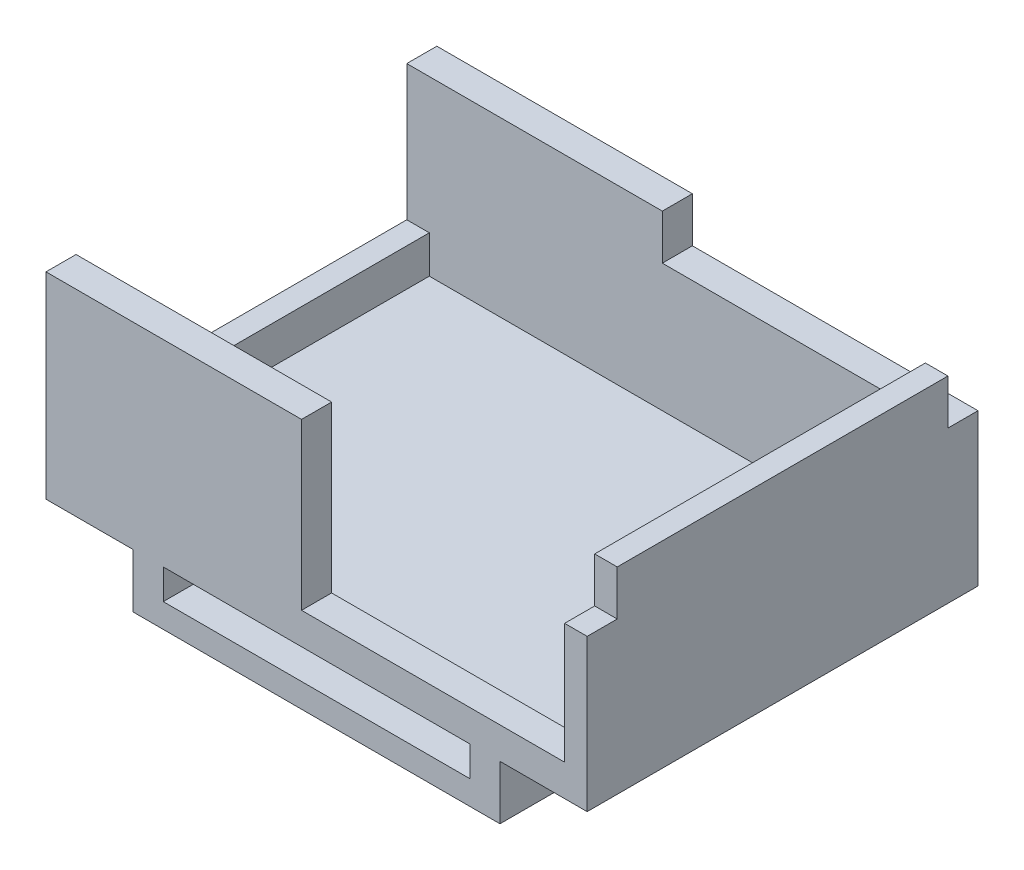
SolidWorks part; units mm, degrees
ref_plane "前视基准面" through (0, 0, 0) normal (0, 0, 1) x (1, 0, 0)
ref_plane "上视基准面" through (0, 0, 0) normal (0, 1, 0) x (1, 0, 0)
ref_plane "右视基准面" through (0, 0, 0) normal (1, 0, 0) x (0, 0, -1)
sketch "草图1" plane through (0, 0, 0) normal (0, 1, 0) x (1, 0, 0)
  line L1 (-18, 13) -> (18, 13)
  line L2 (-18, 13) -> (-18, -13)
  line L3 (-18, -13) -> (18, -13)
  line L4 (18, 13) -> (18, -13)
  line L5 (-18, 13) -> (18, -13) construction
  line L6 (-18, -13) -> (18, 13) construction
  point P0 (0, 0)
extrude "凸台-拉伸1" add sketch "草图1" along normal blind 14.6
sketch "草图2" plane through (0, 14.6, 0) normal (0, 1, 0) x (1, 0, 0)
  line L1 (-16.5, 11) -> (16.5, 11)
  line L2 (-16.5, 11) -> (-16.5, -11)
  line L3 (-16.5, -11) -> (16.5, -11)
  line L4 (16.5, 11) -> (16.5, -11)
  line L5 (-16.5, 11) -> (16.5, -11) construction
  line L6 (-16.5, -11) -> (16.5, 11) construction
  point P0 (0, 0)
extrude "切除-拉伸1" cut sketch "草图2" against normal blind 13
sketch "草图3" plane through (0, 14.6, 0) normal (0, 1, 0) x (1, 0, 0)
  line L1 (-18, 13) -> (18, 13)
  line L2 (-18, 13) -> (-18, -13)
  line L3 (-18, -13) -> (18, -13)
  line L4 (18, 13) -> (18, -13)
extrude "切除-拉伸2" cut sketch "草图3" against normal blind 4.5
sketch "草图4" plane through (0, 10.1, 0) normal (0, 1, 0) x (1, 0, 0)
  line L0 (-18, 13) -> (-18, -13) construction
  line L1 (-16.5, 11) -> (-18, 11)
  line L2 (-16.5, 11) -> (-16.5, -11)
  line L3 (-16.5, -11) -> (-18, -11)
  line L4 (-18, 11) -> (-18, -11)
extrude "切除-拉伸3" cut sketch "草图4" against normal blind 6
sketch "草图5" plane through (0, 0, 0) normal (0, -1, 0) x (-1, 0, 0)
  line L0 (0, 0) -> (0, -13) construction
  line L1 (0, -13) -> (10.2, -13) construction
  line L2 (18, -13) -> (-18, -13) construction
  line L3 (-10.2, -9) -> (-12.2, -9)
  line L4 (10.2, -13) -> (12.2, -13)
  line L5 (10.2, -13) -> (10.2, -9)
  line L6 (10.2, -9) -> (12.2, -9)
  line L7 (12.2, -13) -> (12.2, -9)
  line L8 (-12.2, -13) -> (-12.2, -9)
  line L9 (-10.2, -13) -> (-12.2, -13)
  line L10 (-10.2, -13) -> (-10.2, -9)
  line L11 (0, 0) -> (-2, 0) construction
  line L12 (-10.2, 13) -> (-10.2, 9)
  line L13 (-10.2, 13) -> (-12.2, 13)
  line L14 (-12.2, 13) -> (-12.2, 9)
  line L15 (-10.2, 9) -> (-12.2, 9)
  line L16 (10.2, 9) -> (12.2, 9)
  line L17 (12.2, 13) -> (12.2, 9)
  line L18 (10.2, 13) -> (12.2, 13)
  line L19 (10.2, 13) -> (10.2, 9)
extrude "凸台-拉伸2" add sketch "草图5" along normal blind 2
sketch "草图6" plane through (0, -2, 0) normal (0, -1, 0) x (-1, 0, 0)
  line L1 (12.2, -13) -> (-12.2, -13)
  line L2 (12.2, -13) -> (12.2, -9)
  line L3 (12.2, -9) -> (-12.2, -9)
  line L4 (-12.2, -13) -> (-12.2, -9)
  line L5 (12.2, 9) -> (-12.2, 9)
  line L6 (12.2, 9) -> (12.2, 13)
  line L7 (12.2, 13) -> (-12.2, 13)
  line L8 (-12.2, 9) -> (-12.2, 13)
extrude "凸台-拉伸3" add sketch "草图6" along normal blind 1.6
sketch "草图7" plane through (0, 10.1, 0) normal (0, 1, 0) x (1, 0, 0)
  line L0 (16.5, 11) -> (-16.5, 11) construction
  line L1 (-18, 13) -> (-1, 13)
  line L2 (-18, 13) -> (-18, 11)
  line L3 (-18, 11) -> (-1, 11)
  line L4 (-1, 13) -> (-1, 11)
  line L5 (-18, -13) -> (18, -13) construction
  line L6 (-18, -11) -> (-1, -11)
  line L7 (-18, -11) -> (-18, -13)
  line L8 (-18, -13) -> (-1, -13)
  line L9 (-1, -11) -> (-1, -13)
  line L10 (18, -13) -> (18, 13) construction
  line L11 (16.5, -11) -> (18, -11)
  line L12 (16.5, -11) -> (16.5, 11)
  line L13 (16.5, 11) -> (18, 11)
  line L14 (18, -11) -> (18, 11)
extrude "凸台-拉伸4" add sketch "草图7" along normal blind 3
sketch "草图8" plane through (0, 10.1, 0) normal (0, 1, 0) x (1, 0, 0)
  line L1 (-1, -13) -> (16.5, -13)
  line L2 (-1, -13) -> (-1, -11)
  line L3 (-1, -11) -> (16.5, -11)
  line L4 (16.5, -13) -> (16.5, -11)
extrude "切除-拉伸5" cut sketch "草图8" against normal blind 8
